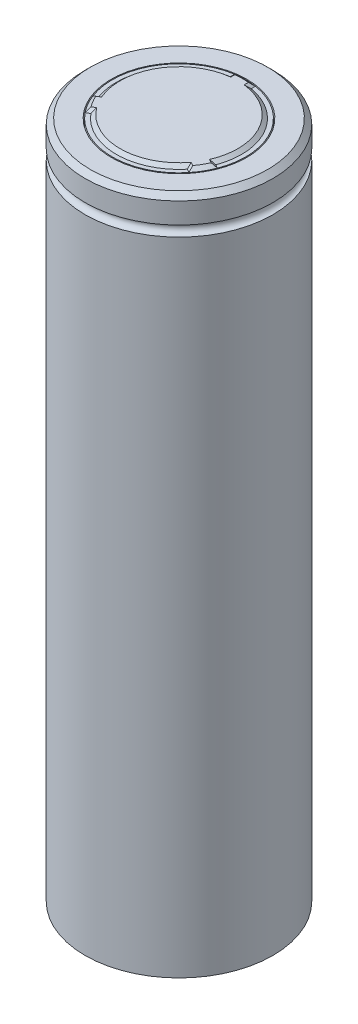
SolidWorks part; units mm, degrees
ref_plane "Спереди" through (0, 0, 0) normal (0, 0, 1) x (1, 0, 0)
ref_plane "Сверху" through (0, 0, 0) normal (0, 1, 0) x (1, 0, 0)
ref_plane "Справа" through (0, 0, 0) normal (1, 0, 0) x (0, 0, -1)
sketch "Эскиз1" plane through (0, 0, 0) normal (0, 1, 0) x (1, 0, 0)
  circle A0 centre (0, 0) radius 9
  dimension "D1" = 18
extrude "Бобышка-Вытянуть1" add sketch "Эскиз1" along normal blind 65
sketch "Эскиз2" plane through (0, 0, 0) normal (0, 0, 1) x (1, 0, 0)
  line L0 (-9, 65) -> (-9, 0) construction
  line L1 (9, 65) -> (-9, 65) construction
  line L2 (0, 0) -> (0, 65) construction
  line L3 (-9, 0) -> (9, 0) construction
  circle A0 centre (-9, 62) radius 0.5
  dimension "D2" = 1
  dimension "D1" = 3
revolve "Вырез-Повернуть1" cut sketch "Эскиз2" angle 360 about L2
chamfer "Фаска1" distance 0.5 angle 45 1 edges at (0, 65, 9)
sketch "Эскиз3" plane through (0, 0, 0) normal (0, -1, 0) x (1, 0, 0)
  circle A0 centre (0, 0) radius 6.5
  circle A1 centre (0, 0) radius 6.4
  dimension "D1" = 13
  dimension "D2" = 0.1
extrude "Вырез-Вытянуть1" cut sketch "Эскиз3" against normal blind 65
sketch "Эскиз4" plane through (0, 65, 0) normal (0, 1, 0) x (1, 0, 0)
  line L0 (-1, 5.9161) -> (-1, 6.3214)
  line L1 (0, -9.9) -> (0, 9.9) construction
  line L2 (1, 5.9161) -> (1, 6.3214)
  line L3 (5.6235, -2.092) -> (5.9745, -2.2947)
  line L4 (4.6235, -3.8241) -> (4.9745, -4.0267)
  line L5 (-4.6235, -3.8241) -> (-4.9745, -4.0267)
  line L6 (-5.6235, -2.092) -> (-5.9745, -2.2947)
  arc A0 (-1, 5.9161) -> (-5.6235, -2.092) centre (0, 0) ccw
  circle A1 centre (0, 0) radius 6.4 construction
  arc A2 (1, 6.3214) -> (-1, 6.3214) centre (0, 0) ccw
  arc A3 (-5.9745, -2.2947) -> (-4.9745, -4.0267) centre (0, 0) ccw
  arc A4 (4.9745, -4.0267) -> (5.9745, -2.2947) centre (0, 0) ccw
  arc A5 (5.6235, -2.092) -> (1, 5.9161) centre (0, 0) ccw
  arc A6 (-4.6235, -3.8241) -> (4.6235, -3.8241) centre (0, 0) ccw
  point P21 (0, 0)
  dimension "D2" = 1
  dimension "D4" = 1
  dimension "D5" = 1
extrude "Бобышка-Вытянуть2" add sketch "Эскиз4" along normal blind 0.3 draft 50
